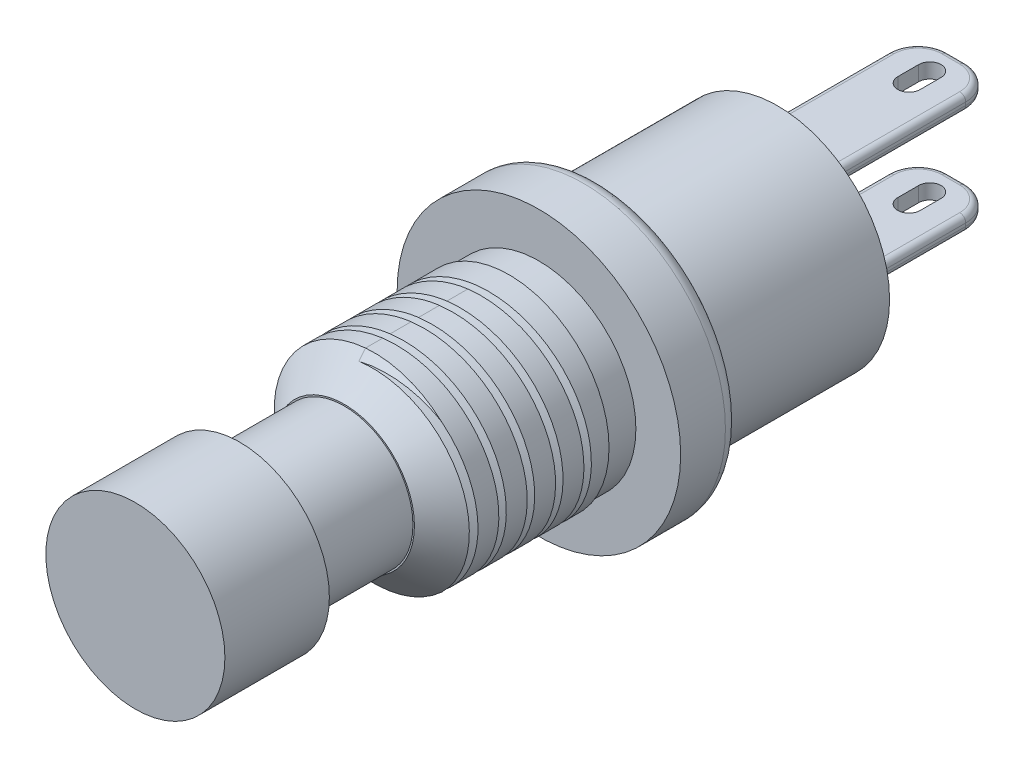
SolidWorks part; units mm, degrees
ref_plane "Front Plane" through (0, 0, 0) normal (0, 0, 1) x (1, 0, 0)
ref_plane "Top Plane" through (0, 0, 0) normal (0, 1, 0) x (1, 0, 0)
ref_plane "Right Plane" through (0, 0, 0) normal (1, 0, 0) x (0, 0, -1)
sketch "Sketch1" plane through (0, 0, 0) normal (0, 0, 1) x (1, 0, 0)
  circle A0 centre (0, 0) radius 3.75
  dimension "D1" = 7.5
extrude "Boss-Extrude1" add sketch "Sketch1" along normal blind 6
sketch "Sketch2" plane through (0, 0, 6) normal (0, 0, 1) x (1, 0, 0)
  circle A0 centre (0, 0) radius 4.75
  dimension "D1" = 9.5
extrude "Boss-Extrude2" add sketch "Sketch2" along normal blind 2
fillet "Fillet1" radius 0.5 1 edges at (4.75, 0, 6)
sketch "Sketch3" plane through (0, 0, 8) normal (0, 0, 1) x (1, 0, 0)
  circle A0 centre (0, 0) radius 3.25
  dimension "D1" = 6.5
extrude "Boss-Extrude3" add sketch "Sketch3" along normal blind 1
sketch "Sketch4" plane through (0, 0, 9) normal (0, 0, 1) x (1, 0, 0)
  circle A0 centre (0, 0) radius 3.35
  dimension "D1" = 6.7
extrude "Boss-Extrude4" add sketch "Sketch4" along normal blind 5.52
chamfer "Chamfer1" distance 1 angle 45 1 edges at (3.35, 0, 14.52)
sketch "Sketch5" plane through (0, 0, 14.52) normal (0, 0, 1) x (1, 0, 0)
  circle A0 centre (0, 0) radius 2.3
  dimension "D1" = 4.6
extrude "Boss-Extrude5" add sketch "Sketch5" along normal blind 3.5
sketch "Sketch6" plane through (0, 0, 18.02) normal (0, 0, 1) x (1, 0, 0)
  circle A0 centre (0, 0) radius 3
  dimension "D1" = 6
extrude "Boss-Extrude6" add sketch "Sketch6" along normal blind 3.5
sketch "Sketch7" plane through (0, 0, 0) normal (0, 0, -1) x (-1, 0, 0)
  line L1 (-1.3, 2.2093) -> (1.3, 2.2093)
  line L2 (-1.3, 2.2093) -> (-1.3, 1.7093)
  line L3 (-1.3, 1.7093) -> (1.3, 1.7093)
  line L4 (1.3, 2.2093) -> (1.3, 1.7093)
  line L5 (-1.3, 2.2093) -> (1.3, 1.7093) construction
  line L6 (-1.3, 1.7093) -> (1.3, 2.2093) construction
  line L7 (-1.3, -1.3001) -> (1.3, -1.3001)
  line L8 (-1.3, -1.3001) -> (-1.3, -1.8001)
  line L9 (-1.3, -1.8001) -> (1.3, -1.8001)
  line L10 (1.3, -1.3001) -> (1.3, -1.8001)
  line L11 (-1.3, -1.3001) -> (1.3, -1.8001) construction
  line L12 (-1.3, -1.8001) -> (1.3, -1.3001) construction
  point P0 (0, 1.9593)
  point P5 (0, -1.5501)
  dimension "D1" = 2.6
  dimension "D2" = 2.6
  dimension "D3" = 0.5
  dimension "D4" = 0.5
  dimension "D5" = 0
  dimension "D6" = 0
extrude "Boss-Extrude7" add sketch "Sketch7" along normal blind 6
fillet "Fillet4" radius 1 4 edges at (1.3, 1.9593, -6) (-1.3, 1.9593, -6) (-1.3, -1.5501, -6) (1.3, -1.5501, -6)
sketch "Sketch8" plane through (0, -1.8001, 0) normal (0, -1, 0) x (1, 0, 0)
  line L0 (0, -4.4) -> (0, -5.1) construction
  line L1 (0.375, -4.4) -> (0.375, -5.1)
  line L2 (-0.375, -4.4) -> (-0.375, -5.1)
  line L3 (0.3, -6) -> (-0.3, -6) construction
  arc A0 (0.375, -4.4) -> (-0.375, -4.4) centre (0, -4.4) ccw
  arc A1 (-0.375, -5.1) -> (0.375, -5.1) centre (0, -5.1) ccw
  point P3 (0, -4.75)
  dimension "D1" = 0.7
  dimension "D2" = 0.75
  dimension "D3" = 0.9
extrude "Cut-Extrude1" cut sketch "Sketch8" against normal blind 6
fillet "Fillet5" radius 0.2 20 edges at (-1.3, 2.2093, -2.5) (-1.0071, 2.2093, -5.7071) (0, 2.2093, -6) (1.0071, 2.2093, -5.7071) (-1.3, -1.3001, -2.5) (-1.0071, -1.3001, -5.7071) (0, -1.3001, -6) (1.0071, -1.3001, -5.7071) (-1.3, -1.8001, -2.5) (-1.0071, -1.8001, -5.7071) (0, -1.8001, -6) (1.0071, -1.8001, -5.7071) (1.3, 1.7093, -2.5) (1.0071, 1.7093, -5.7071) (0, 1.7093, -6) (-1.0071, 1.7093, -5.7071) (1.3, 2.2093, -2.5) (1.3, -1.3001, -2.5) (1.3, -1.8001, -2.5) (-1.3, 1.7093, -2.5)
sketch "Sketch9" plane through (0, 0, 0) normal (0, 1, 0) x (1, 0, 0)
  line L0 (3.1, -13.52) -> (4.1, -13.02)
  line L1 (3.35, -13.52) -> (-3.35, -13.52) construction
  line L2 (4.1, -13.02) -> (4.1, -14.02)
  line L3 (4.1, -14.02) -> (3.1, -13.52)
  line L4 (3.1, -13.52) -> (4.367, -13.52) construction
  line L5 (3.35, -13.52) -> (3.35, -9) construction
  dimension "D1" = 1
  dimension "D2" = 0.5
  dimension "D3" = 1
  dimension "D4" = 0.25
sketch "Sketch10" plane through (0, 0, 14.52) normal (0, 0, 1) x (1, 0, 0)
  circle A0 centre (0, 0) radius 3.35
curve "Helix/Spiral1" pitch 0.95 height 5.4625 turns 5.75
sweep "Cut-Sweep1" cut profiles "Sketch9" path "Helix/Spiral1"
